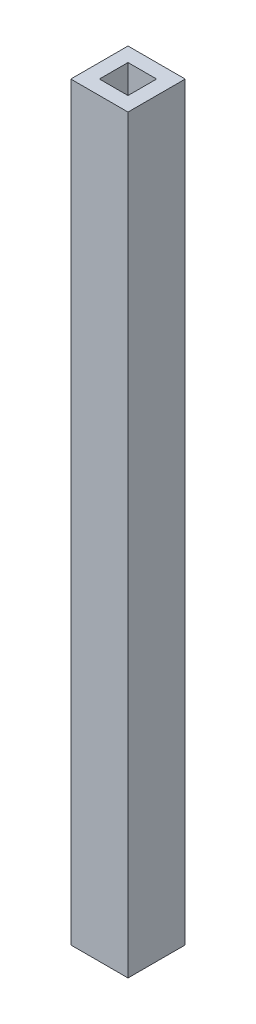
SolidWorks part; units mm, degrees
material "Gray Cast Iron"
ref_plane "Front Plane" through (0, 0, 0) normal (0, 0, 1) x (1, 0, 0)
ref_plane "Top Plane" through (0, 0, 0) normal (0, 1, 0) x (1, 0, 0)
ref_plane "Right Plane" through (0, 0, 0) normal (1, 0, 0) x (0, 0, -1)
sketch "Sketch3" plane through (0, 0, 0) normal (0, 1, 0) x (1, 0, 0)
  line L0 (0, 0) -> (25.4, 0)
  line L1 (25.4, 0) -> (25.4, 25.4)
  line L2 (25.4, 25.4) -> (0, 25.4)
  line L3 (0, 25.4) -> (0, 0)
  line L4 (6.35, 19.05) -> (6.35, 6.35)
  line L5 (6.35, 6.35) -> (19.05, 6.35)
  line L6 (19.05, 6.35) -> (19.05, 19.05)
  line L7 (19.05, 19.05) -> (6.35, 19.05)
  dimension "D2" = 6.35
  dimension "D3" = 25.4
extrude "Boss-Extrude2" add sketch "Sketch3" along normal blind 333
equation "\"D\"= 1'in"
equation "\"H\"= 1'in"
equation "\"elongation\"= .01'in"
equation "\"E\"= 16650000'in"
equation "\"T\"= .25'in"
equation "\"F\"= 375'in"
equation "\"A\"= 4 * \"H\" * \"T\" - 4 * \"T\" ^ 2'in"
equation "\"L\"= ( \"A\" * \"E\" * \"elongation\" ) / \"F\"'in"
equation "\"D1@Boss-Extrude2\"=\"L\""
